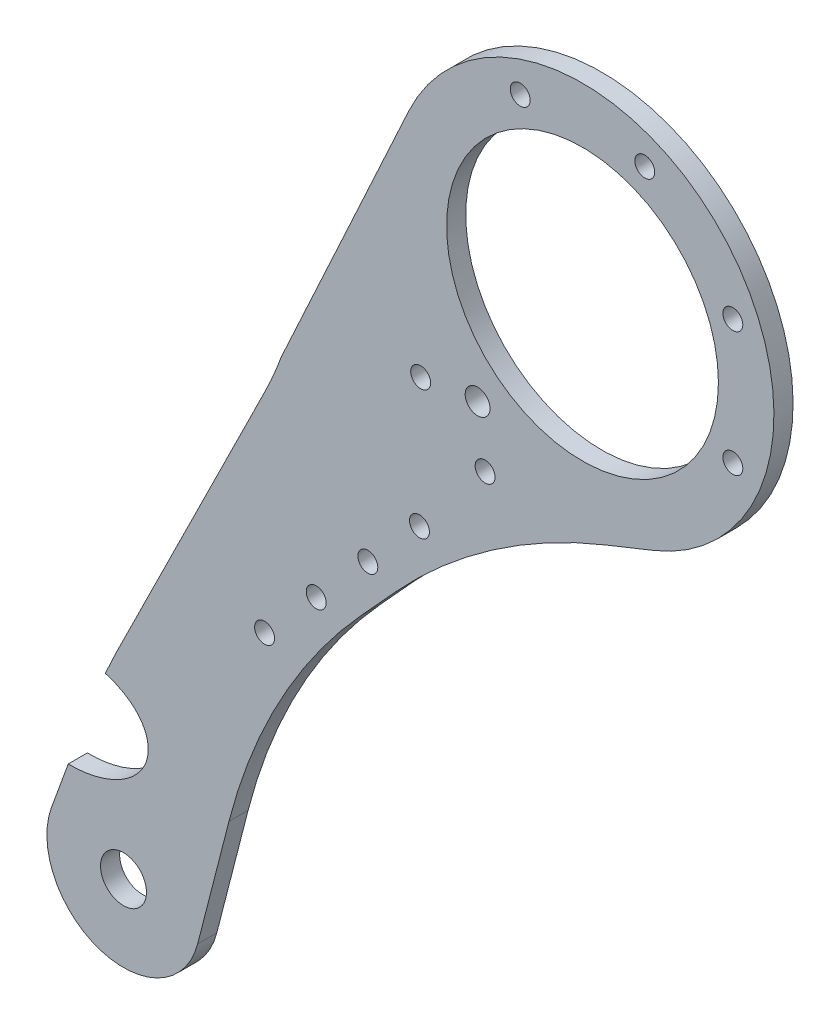
SolidWorks part; units mm, degrees
ref_plane "前视基准面" through (0, 0, 0) normal (0, 0, 1) x (1, 0, 0)
ref_plane "上视基准面" through (0, 0, 0) normal (0, 1, 0) x (1, 0, 0)
ref_plane "右视基准面" through (0, 0, 0) normal (1, 0, 0) x (0, 0, -1)
other "Configuration Table"
sketch "草图1" plane through (0, 0, 0) normal (0, 0, 1) x (1, 0, 0)
  line L0 (-22.2156, 27.6044) -> (-54.7044, -38.0031)
  line L1 (-3.1022, 20.9519) -> (-14.7998, 29.4335)
  line L2 (-51.4351, -40.2391) -> (-2.3446, 13.5329)
  line L3 (0.3583, 100.9163) -> (-32.8546, 28.8219)
  line L4 (-37.2098, 18.6469) -> (-75.1569, -57.9829)
  line L5 (-88.5355, -91.1588) -> (-92.9017, -103.1549)
  line L6 (-55.707, -117.8314) -> (-35.5281, -70.4474)
  line L7 (17.8245, -2.9402) -> (75.5374, 39.8211)
  circle A3 centre (-74.1079, -109.9953) radius 6
  circle A7 centre (20.3346, 29.4227) radius 2.6
  circle A8 centre (3.505, 42.3365) radius 2.6
  circle A9 centre (75.823, 110.0473) radius 1.85 construction
  arc A10 (-54.7044, -38.0031) -> (-51.4351, -40.2391) centre (-52.9121, -38.8906) ccw
  arc A11 (-14.7998, 29.4335) -> (-22.2156, 27.6044) centre (-17.7349, 25.3855) ccw
  arc A12 (-2.3446, 13.5329) -> (-3.1022, 20.9519) centre (-6.0372, 16.904) ccw
  circle A13 centre (45.771, 79.9953) radius 37.5
  circle A14 centre (-37.2593, -35.8353) radius 2.6
  circle A15 centre (-10.2902, -6.2943) radius 2.6
  circle A16 centre (-23.7748, -21.0648) radius 2.6
  circle A17 centre (3.1943, 8.4762) radius 2.6
  arc A18 (-37.2098, 18.6469) -> (-32.8546, 28.8219) centre (-126.8239, 63.0239) ccw
  arc A19 (-75.1569, -57.9829) -> (-78.8302, -65.8229) centre (104.0713, -146.7367) ccw
  arc A20 (-92.9017, -103.1549) -> (-55.707, -117.8314) centre (-74.1079, -109.9953) ccw
  arc A21 (-11.4018, -28.6532) -> (-35.5281, -70.4474) centre (148.4812, -148.8091) ccw
  arc A22 (17.8245, -2.9402) -> (-11.4018, -28.6532) centre (134.692, -165.2424) ccw
  arc A23 (75.5374, 39.8211) -> (0.3583, 100.9163) centre (45.771, 79.9953) ccw
  ellipse E0 centre (-87.2474, -77.9723) end of major axis (-106.8446, -79.0236) minor radius 13.1666 (-88.5355, -91.1588) -> (-78.8302, -65.8229) ccw
extrude "凸台-拉伸1" add sketch "草图1" along normal blind 5
sketch "草图3" plane through (0, 0, 5) normal (0, 0, 1) x (1, 0, 0)
  line L0 (45.771, 79.9953) -> (75.823, 110.0473)
  line L1 (45.771, 79.9953) -> (62.035, 119.2602)
  line L3 (-3.1022, 20.9519) -> (-14.7998, 29.4335)
  line L4 (-51.4351, -40.2391) -> (-2.3446, 13.5329)
  line L5 (-22.2156, 27.6044) -> (-54.7044, -38.0031)
  line L6 (-3.1022, 20.9519) -> (-14.7998, 29.4335)
  line L7 (-51.4351, -40.2391) -> (-2.3446, 13.5329)
  line L8 (-22.2156, 27.6044) -> (-54.7044, -38.0031)
  line L11 (-88.5355, -91.1588) -> (-92.9017, -103.1549)
  line L12 (-37.2098, 18.6469) -> (-75.1569, -57.9829)
  line L13 (0.3583, 100.9163) -> (-32.8546, 28.8219)
  line L14 (17.8245, -2.9402) -> (75.5374, 39.8211)
  line L15 (-55.707, -117.8314) -> (-35.5281, -70.4474)
  line L16 (-88.5355, -91.1588) -> (-92.9017, -103.1549)
  line L17 (-37.2098, 18.6469) -> (-75.1569, -57.9829)
  line L18 (0.3583, 100.9163) -> (-32.8546, 28.8219)
  line L19 (17.8245, -2.9402) -> (75.5374, 39.8211)
  line L20 (-55.707, -117.8314) -> (-35.5281, -70.4474)
  circle A0 centre (75.823, 110.0473) radius 1.85 construction
  circle A1 centre (-74.1079, -109.9953) radius 6
  circle A2 centre (-74.1079, -109.9953) radius 6
  circle A3 centre (3.505, 42.3365) radius 2.6
  circle A4 centre (3.505, 42.3365) radius 2.6
  circle A5 centre (20.3346, 29.4227) radius 2.6
  circle A6 centre (20.3346, 29.4227) radius 2.6
  circle A7 centre (3.1943, 8.4762) radius 2.6
  circle A8 centre (3.1943, 8.4762) radius 2.6
  arc A9 (-14.7998, 29.4335) -> (-22.2156, 27.6044) centre (-17.7349, 25.3855) ccw
  arc A10 (-2.3446, 13.5329) -> (-3.1022, 20.9519) centre (-6.0372, 16.904) ccw
  arc A11 (-54.7044, -38.0031) -> (-51.4351, -40.2391) centre (-52.9121, -38.8906) ccw
  arc A12 (-14.7998, 29.4335) -> (-22.2156, 27.6044) centre (-17.7349, 25.3855) ccw
  arc A13 (-2.3446, 13.5329) -> (-3.1022, 20.9519) centre (-6.0372, 16.904) ccw
  arc A14 (-54.7044, -38.0031) -> (-51.4351, -40.2391) centre (-52.9121, -38.8906) ccw
  circle A15 centre (-23.7748, -21.0648) radius 2.6
  circle A16 centre (-23.7748, -21.0648) radius 2.6
  circle A17 centre (-10.2902, -6.2943) radius 2.6
  circle A18 centre (-10.2902, -6.2943) radius 2.6
  circle A19 centre (-37.2593, -35.8353) radius 2.6
  circle A20 centre (-37.2593, -35.8353) radius 2.6
  circle A21 centre (45.771, 79.9953) radius 37.5
  circle A22 centre (45.771, 79.9953) radius 37.5
  circle A23 centre (75.823, 110.0473) radius 1.85
  circle A24 centre (45.771, 79.9953) radius 42.5
  circle A25 centre (62.035, 119.2602) radius 2.6
  circle A26 centre (85.0359, 96.2593) radius 2.6
  circle A27 centre (85.0359, 63.7312) radius 2.6
  arc A28 (-75.1569, -57.9829) -> (-78.8302, -65.8229) centre (104.0713, -146.7367) ccw
  arc A29 (-37.2098, 18.6469) -> (-32.8546, 28.8219) centre (-126.8239, 63.0239) ccw
  arc A30 (75.5374, 39.8211) -> (0.3583, 100.9163) centre (45.771, 79.9953) ccw
  arc A31 (17.8245, -2.9402) -> (-11.4018, -28.6532) centre (134.692, -165.2424) ccw
  arc A32 (-11.4018, -28.6532) -> (-35.5281, -70.4474) centre (148.4812, -148.8091) ccw
  arc A33 (-92.9017, -103.1549) -> (-55.707, -117.8314) centre (-74.1079, -109.9953) ccw
  arc A34 (-75.1569, -57.9829) -> (-78.8302, -65.8229) centre (104.0713, -146.7367) ccw
  arc A35 (-37.2098, 18.6469) -> (-32.8546, 28.8219) centre (-126.8239, 63.0239) ccw
  arc A36 (75.5374, 39.8211) -> (0.3583, 100.9163) centre (45.771, 79.9953) ccw
  arc A37 (17.8245, -2.9402) -> (-11.4018, -28.6532) centre (134.692, -165.2424) ccw
  arc A38 (-11.4018, -28.6532) -> (-35.5281, -70.4474) centre (148.4812, -148.8091) ccw
  arc A39 (-92.9017, -103.1549) -> (-55.707, -117.8314) centre (-74.1079, -109.9953) ccw
  circle A40 centre (62.035, 40.7304) radius 2.6
  circle A41 centre (29.5069, 40.7304) radius 2.6
  circle A42 centre (6.5061, 63.7312) radius 2.6
  circle A43 centre (6.5061, 96.2593) radius 2.6
  circle A44 centre (29.5069, 119.2602) radius 2.6
  ellipse E1 centre (-87.2474, -77.9723) end of major axis (-67.6501, -76.921) minor radius 13.1666 (-88.5355, -91.1588) -> (-78.8302, -65.8229) ccw
  ellipse E2 centre (-87.2474, -77.9723) end of major axis (-67.6501, -76.921) minor radius 13.1666 (-88.5355, -91.1588) -> (-78.8302, -65.8229) ccw
  point P83 (45.771, 79.9953)
  dimension "D11" = 85
  dimension "D13" = 5.2
  dimension "D12" = 22.5
  dimension "D1" = 0
  dimension "D2" = 0
  dimension "D3" = 0
  dimension "D4" = 0
  dimension "D5" = 0
  dimension "D6" = 0
  dimension "D7" = 0
  dimension "D8" = 0
  dimension "D9" = 0
  dimension "D10" = 0
  dimension "D14" = 8
extrude "切除-拉伸1" cut sketch "草图3" against normal blind 5 contours A24 A44 | A24 A44 | A24 A25 | L1 A25 A24 | A24 A25 L1 | A24 A26 | A24 A26 | A24 A27 | A24 A27
sketch "草图4" plane through (0, 0, 5) normal (0, 0, 1) x (1, 0, 0)
  line L0 (3.505, 42.3365) -> (20.3346, 29.4227)
  line L1 (45.771, 79.9953) -> (11.9198, 35.8796)
  circle A0 centre (20.3346, 29.4227) radius 2.6 construction
  circle A1 centre (3.505, 42.3365) radius 2.6 construction
  circle A2 centre (20.3346, 29.4227) radius 2.6
  circle A3 centre (3.505, 42.3365) radius 2.6
  circle A4 centre (45.771, 79.9953) radius 37.5 construction
  circle A5 centre (45.771, 79.9953) radius 37.5
  circle A6 centre (18.3767, 44.2944) radius 3.25
  dimension "D2" = 6.5
  dimension "D1" = 45
extrude "切除-拉伸2" cut sketch "草图4" against normal blind 5 contours A6
sketch "草图5" plane through (0, 0, 5) normal (0, 0, 1) x (1, 0, 0)
  line L0 (-37.2593, -35.8353) -> (3.1943, 8.4762)
  line L1 (-37.2593, -46.9591) -> (20.05, 15.8154)
  line L2 (64.3765, 33.5858) -> (20.05, 15.8154)
  line L3 (-37.2593, -46.9591) -> (-54.7373, -114.9731)
  line L8 (0.3583, 100.9163) -> (-32.8546, 28.8219)
  line L9 (-37.2098, 18.6469) -> (-75.1569, -57.9829)
  line L10 (-88.5355, -91.1588) -> (-92.9017, -103.1549)
  line L11 (-55.707, -117.8314) -> (-35.5281, -70.4474)
  line L12 (17.8245, -2.9402) -> (75.5374, 39.8211)
  line L13 (0.3583, 100.9163) -> (-32.8546, 28.8219)
  line L14 (-37.2098, 18.6469) -> (-75.1569, -57.9829)
  line L15 (-88.5355, -91.1588) -> (-92.9017, -103.1549)
  line L16 (-55.707, -117.8314) -> (-35.5281, -70.4474)
  line L17 (17.8245, -2.9402) -> (75.5374, 39.8211)
  arc A0 (75.5374, 39.8211) -> (0.3583, 100.9163) centre (45.771, 79.9953) ccw construction
  circle A1 centre (45.771, 79.9953) radius 50
  circle A2 centre (-74.1079, -109.9953) radius 6 construction
  circle A3 centre (-74.1079, -109.9953) radius 6
  circle A4 centre (-74.1079, -109.9953) radius 20
  arc A11 (75.5374, 39.8211) -> (0.3583, 100.9163) centre (45.771, 79.9953) ccw
  arc A12 (-37.2098, 18.6469) -> (-32.8546, 28.8219) centre (-126.8239, 63.0239) ccw
  arc A13 (-75.1569, -57.9829) -> (-78.8302, -65.8229) centre (104.0713, -146.7367) ccw
  arc A14 (-92.9017, -103.1549) -> (-55.707, -117.8314) centre (-74.1079, -109.9953) ccw
  arc A15 (-11.4018, -28.6532) -> (-35.5281, -70.4474) centre (148.4812, -148.8091) ccw
  arc A16 (17.8245, -2.9402) -> (-11.4018, -28.6532) centre (134.692, -165.2424) ccw
  arc A17 (75.5374, 39.8211) -> (0.3583, 100.9163) centre (45.771, 79.9953) ccw
  arc A18 (-37.2098, 18.6469) -> (-32.8546, 28.8219) centre (-126.8239, 63.0239) ccw
  arc A19 (-75.1569, -57.9829) -> (-78.8302, -65.8229) centre (104.0713, -146.7367) ccw
  arc A20 (-92.9017, -103.1549) -> (-55.707, -117.8314) centre (-74.1079, -109.9953) ccw
  arc A21 (-11.4018, -28.6532) -> (-35.5281, -70.4474) centre (148.4812, -148.8091) ccw
  arc A22 (17.8245, -2.9402) -> (-11.4018, -28.6532) centre (134.692, -165.2424) ccw
  ellipse E1 centre (-87.2474, -77.9723) end of major axis (-67.6501, -76.921) minor radius 13.1666 (-88.5355, -91.1588) -> (-78.8302, -65.8229) ccw
  ellipse E2 centre (-87.2474, -77.9723) end of major axis (-67.6501, -76.921) minor radius 13.1666 (-88.5355, -91.1588) -> (-78.8302, -65.8229) ccw
  line M34 (-55.707, -117.8314) -> (-35.5281, -70.4474)
  arc M35 (-35.5281, -70.4474) -> (-11.4018, -28.6532) centre (148.4812, -148.8091) cw
  arc M36 (-11.4018, -28.6532) -> (17.8245, -2.9402) centre (134.692, -165.2424) cw
  line M37 (17.8245, -2.9402) -> (75.5374, 39.8211)
  dimension "D1" = 7.5
  dimension "D3" = 85
  dimension "D2" = 0
extrude "切除-拉伸3" cut sketch "草图5" against normal blind 10 contours A4 A1 L2 L1 L3 M34 M35 M36 M37
fillet "圆角1" radius 150 2 edges at (20.05, 15.8154, 2.5) (-37.2593, -46.9591, 2.5)
sketch "草图7" plane through (0, 0, 5) normal (0, 0, 1) x (1, 0, 0)
  line L6 (-54.7373, -114.9731) -> (-46.5615, -83.1577)
  line L7 (-12.0603, -19.357) -> (-3.0757, -9.5156)
  line L8 (51.8865, 28.5786) -> (64.3765, 33.5858)
  line L9 (0.3583, 100.9163) -> (-32.8546, 28.8219)
  line L10 (-37.2098, 18.6469) -> (-75.1569, -57.9829)
  line L11 (-88.5355, -91.1588) -> (-92.9017, -103.1549)
  line L12 (-54.7373, -114.9731) -> (-46.5615, -83.1577)
  line L13 (-12.0603, -19.357) -> (-3.0757, -9.5156)
  line L14 (51.8865, 28.5786) -> (64.3765, 33.5858)
  line L15 (0.3583, 100.9163) -> (-32.8546, 28.8219)
  line L16 (-37.2098, 18.6469) -> (-75.1569, -57.9829)
  line L17 (-88.5355, -91.1588) -> (-92.9017, -103.1549)
  arc A6 (-92.9017, -103.1549) -> (-54.7373, -114.9731) centre (-74.1079, -109.9953) ccw
  arc A7 (-12.0603, -19.357) -> (-46.5615, -83.1577) centre (98.7183, -120.4911) ccw
  arc A8 (51.8865, 28.5786) -> (-3.0757, -9.5156) centre (107.7029, -110.6497) ccw
  arc A9 (64.3765, 33.5858) -> (0.3583, 100.9163) centre (45.771, 79.9953) ccw
  arc A10 (-37.2098, 18.6469) -> (-32.8546, 28.8219) centre (-126.8239, 63.0239) ccw
  arc A11 (-75.1569, -57.9829) -> (-78.8302, -65.8229) centre (104.0713, -146.7367) ccw
  arc A12 (-92.9017, -103.1549) -> (-54.7373, -114.9731) centre (-74.1079, -109.9953) ccw
  arc A13 (-12.0603, -19.357) -> (-46.5615, -83.1577) centre (98.7183, -120.4911) ccw
  arc A14 (51.8865, 28.5786) -> (-3.0757, -9.5156) centre (107.7029, -110.6497) ccw
  arc A15 (64.3765, 33.5858) -> (0.3583, 100.9163) centre (45.771, 79.9953) ccw
  arc A16 (-37.2098, 18.6469) -> (-32.8546, 28.8219) centre (-126.8239, 63.0239) ccw
  arc A17 (-75.1569, -57.9829) -> (-78.8302, -65.8229) centre (104.0713, -146.7367) ccw
  ellipse E1 centre (-87.2474, -77.9723) end of major axis (-67.6501, -76.921) minor radius 13.1666 (-88.5355, -91.1588) -> (-78.8302, -65.8229) ccw
  ellipse E2 centre (-87.2474, -77.9723) end of major axis (-67.6501, -76.921) minor radius 13.1666 (-88.5355, -91.1588) -> (-78.8302, -65.8229) ccw
  dimension "D1" = 0
sketch "草图9" plane through (0, 0, 5) normal (0, 0, 1) x (1, 0, 0)
  line L3 (-51.4351, -40.2391) -> (-2.3446, 13.5329)
  line L4 (-22.2156, 27.6044) -> (-54.7044, -38.0031)
  line L5 (-3.1022, 20.9519) -> (-14.7998, 29.4335)
  line L6 (-51.4351, -40.2391) -> (-2.3446, 13.5329)
  line L7 (-22.2156, 27.6044) -> (-54.7044, -38.0031)
  line L8 (-3.1022, 20.9519) -> (-14.7998, 29.4335)
  circle A1 centre (18.3767, 44.2944) radius 3.25
  circle A2 centre (18.3767, 44.2944) radius 3.25
  circle A3 centre (20.3346, 29.4227) radius 2.6
  circle A4 centre (20.3346, 29.4227) radius 2.6
  arc A5 (-54.7044, -38.0031) -> (-51.4351, -40.2391) centre (-52.9121, -38.8906) ccw
  arc A6 (-14.7998, 29.4335) -> (-22.2156, 27.6044) centre (-17.7349, 25.3855) ccw
  arc A7 (-2.3446, 13.5329) -> (-3.1022, 20.9519) centre (-6.0372, 16.904) ccw
  arc A8 (-54.7044, -38.0031) -> (-51.4351, -40.2391) centre (-52.9121, -38.8906) ccw
  arc A9 (-14.7998, 29.4335) -> (-22.2156, 27.6044) centre (-17.7349, 25.3855) ccw
  arc A10 (-2.3446, 13.5329) -> (-3.1022, 20.9519) centre (-6.0372, 16.904) ccw
  circle A11 centre (45.771, 79.9953) radius 37.5
  circle A12 centre (45.771, 79.9953) radius 37.5
  circle A13 centre (-10.2902, -6.2943) radius 2.6
  circle A14 centre (-10.2902, -6.2943) radius 2.6
  circle A15 centre (3.1943, 8.4762) radius 2.6
  circle A16 centre (3.1943, 8.4762) radius 2.6
  circle A17 centre (29.5069, 119.2602) radius 2.6
  circle A18 centre (29.5069, 119.2602) radius 2.6
  circle A19 centre (62.035, 119.2602) radius 2.6
  circle A20 centre (62.035, 119.2602) radius 2.6
  circle A21 centre (85.0359, 96.2593) radius 2.6
  circle A22 centre (85.0359, 96.2593) radius 2.6
  circle A23 centre (85.0359, 63.7312) radius 2.6
  circle A24 centre (85.0359, 63.7312) radius 2.6
  circle A25 centre (-23.7748, -21.0648) radius 2.6
  circle A26 centre (-23.7748, -21.0648) radius 2.6
  circle A27 centre (-37.2593, -35.8353) radius 2.6
  circle A28 centre (-37.2593, -35.8353) radius 2.6
  circle A29 centre (3.505, 42.3365) radius 2.6
  circle A30 centre (3.505, 42.3365) radius 2.6
  circle A31 centre (-74.1079, -109.9953) radius 6
  circle A32 centre (-74.1079, -109.9953) radius 6
  dimension "D1" = 0
  dimension "D2" = 0
  dimension "D3" = 0
  dimension "D4" = 0
  dimension "D5" = 0
  dimension "D6" = 0
  dimension "D7" = 0
  dimension "D8" = 0
  dimension "D9" = 0
  dimension "D10" = 0
  dimension "D11" = 0
  dimension "D12" = 0
  dimension "D13" = 0
  dimension "D14" = 0
extrude "凸台-拉伸3" add sketch "草图9" against normal through all contours L6 A10 L8 A9 L7 A8
sketch "草图10" plane through (0, 0, 5) normal (0, 0, 1) x (1, 0, 0)
  line L6 (-54.7373, -114.9731) -> (-46.5615, -83.1577)
  line L7 (-12.0603, -19.357) -> (-3.0757, -9.5156)
  line L8 (51.8865, 28.5786) -> (64.3765, 33.5858)
  line L9 (0.3583, 100.9163) -> (-32.8546, 28.8219)
  line L10 (-37.2098, 18.6469) -> (-75.1569, -57.9829)
  line L11 (-88.5355, -91.1588) -> (-92.9017, -103.1549)
  line L12 (-54.7373, -114.9731) -> (-46.5615, -83.1577)
  line L13 (-12.0603, -19.357) -> (-3.0757, -9.5156)
  line L14 (51.8865, 28.5786) -> (64.3765, 33.5858)
  line L15 (0.3583, 100.9163) -> (-32.8546, 28.8219)
  line L16 (-37.2098, 18.6469) -> (-75.1569, -57.9829)
  line L17 (-88.5355, -91.1588) -> (-92.9017, -103.1549)
  circle A0 centre (45.771, 79.9953) radius 35.5
  circle A1 centre (45.771, 79.9953) radius 37.5 construction
  circle A2 centre (45.771, 79.9953) radius 37.5
  arc A6 (-92.9017, -103.1549) -> (-54.7373, -114.9731) centre (-74.1079, -109.9953) ccw
  arc A7 (-12.0603, -19.357) -> (-46.5615, -83.1577) centre (98.7183, -120.4911) ccw
  arc A8 (51.8865, 28.5786) -> (-3.0757, -9.5156) centre (107.7029, -110.6497) ccw
  arc A9 (64.3765, 33.5858) -> (0.3583, 100.9163) centre (45.771, 79.9953) ccw
  arc A10 (-37.2098, 18.6469) -> (-32.8546, 28.8219) centre (-126.8239, 63.0239) ccw
  arc A11 (-75.1569, -57.9829) -> (-78.8302, -65.8229) centre (104.0713, -146.7367) ccw
  arc A12 (-92.9017, -103.1549) -> (-54.7373, -114.9731) centre (-74.1079, -109.9953) ccw
  arc A13 (-12.0603, -19.357) -> (-46.5615, -83.1577) centre (98.7183, -120.4911) ccw
  arc A14 (51.8865, 28.5786) -> (-3.0757, -9.5156) centre (107.7029, -110.6497) ccw
  arc A15 (64.3765, 33.5858) -> (0.3583, 100.9163) centre (45.771, 79.9953) ccw
  arc A16 (-37.2098, 18.6469) -> (-32.8546, 28.8219) centre (-126.8239, 63.0239) ccw
  arc A17 (-75.1569, -57.9829) -> (-78.8302, -65.8229) centre (104.0713, -146.7367) ccw
  ellipse E1 centre (-87.2474, -77.9723) end of major axis (-67.6501, -76.921) minor radius 13.1666 (-88.5355, -91.1588) -> (-78.8302, -65.8229) ccw
  ellipse E2 centre (-87.2474, -77.9723) end of major axis (-67.6501, -76.921) minor radius 13.1666 (-88.5355, -91.1588) -> (-78.8302, -65.8229) ccw
  dimension "D2" = 2
  dimension "D1" = 0
extrude "凸台-拉伸4" add sketch "草图10" against normal through all
move or copy body "实体-移动/复制1" [suppressed] bodies to move or copy 112 parameters "D1"=0, "D2"=0, "D3"=0
move or copy body "实体-移动/复制2" [suppressed] bodies to move or copy 113 parameters "D1"=0, "D2"=0, "D3"=0
